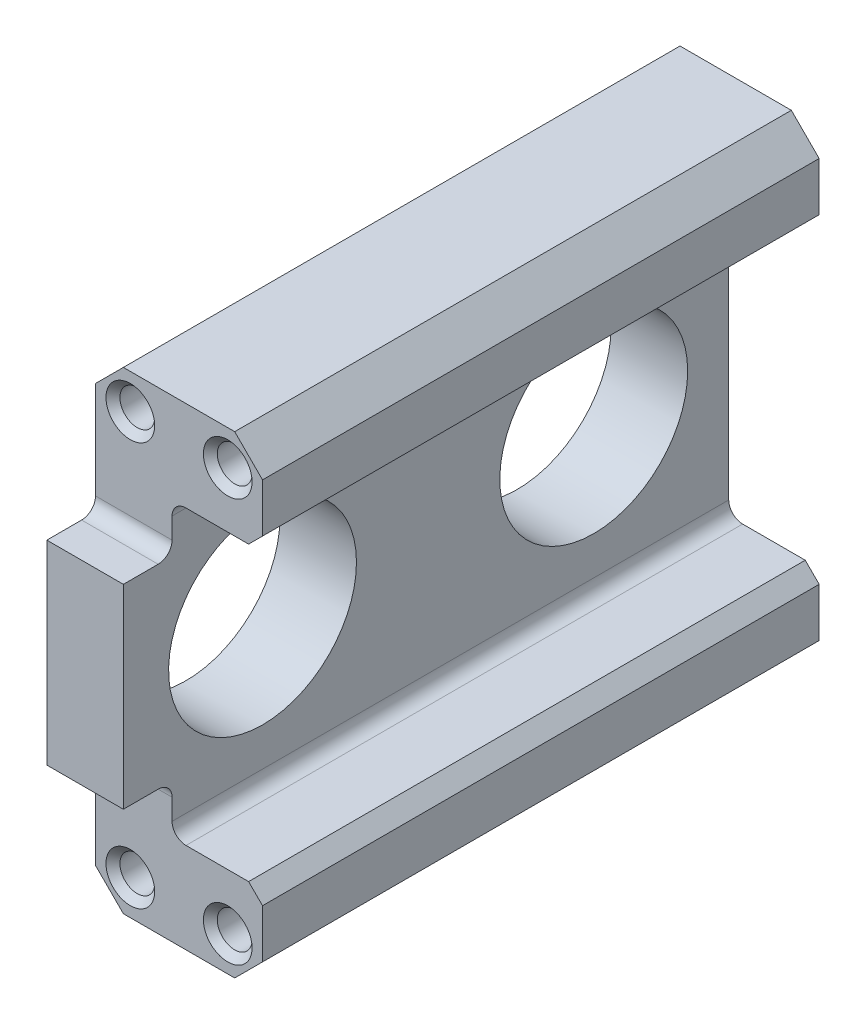
SolidWorks part; units mm, degrees
material "7075-O (SS)"
ref_plane "前视基准面" through (0, 0, 0) normal (0, 0, 1) x (1, 0, 0)
ref_plane "上视基准面" through (0, 0, 0) normal (0, 1, 0) x (1, 0, 0)
ref_plane "右视基准面" through (0, 0, 0) normal (1, 0, 0) x (0, 0, -1)
sketch "草图1" plane through (0, 0, 0) normal (0, 0, 1) x (1, 0, 0)
  line L1 (-6, -17) -> (6, -17)
  line L2 (-6, -17) -> (-6, 17)
  line L3 (-6, 17) -> (6, 17)
  line L4 (6, -17) -> (6, 17)
  line L5 (-6, -17) -> (6, 17) construction
  line L6 (-6, 17) -> (6, -17) construction
  point P0 (0, 0)
  dimension "D1" = 12
  dimension "D2" = 34
extrude "凸台-拉伸1" add sketch "草图1" along normal blind 43.5
sketch "草图3" plane through (6, 0, 0) normal (1, 0, 0) x (0, 0, -1)
  line L0 (-43.5, -17) -> (-43.5, 17) construction
  circle A0 centre (-33.5, 0) radius 6.75
  circle A1 centre (-9.7, 0) radius 6.75
  dimension "D1" = 13.5
  dimension "D2" = 10
  dimension "D3" = 33.8
extrude "切除-拉伸1" cut sketch "草图3" against normal through all
sketch "草图4" plane through (0, 0, 43.5) normal (0, 0, 1) x (1, 0, 0)
  line L0 (-6, 17) -> (-6, -17) construction
  line L1 (6, 17) -> (-6, 17)
  line L2 (6, 17) -> (6, 7)
  line L3 (6, 7) -> (-6, 7)
  line L4 (-6, 17) -> (-6, 7)
  dimension "D1" = 10
extrude "切除-拉伸2" cut sketch "草图4" against normal blind 3.5
mirror "镜向1" about plane through (0, 0, 0) normal (0, 1, 0) of "切除-拉伸2"
fillet "圆角1" radius 1 2 edges at (0, -7, 40) (0, 7, 40)
hole_wizard "M3 螺纹孔1" positions "草图6" profile "草图5" tap size "M3" standard "GB"
sketch "草图6" plane through (0, 0, 40) normal (0, 0, 1) x (1, 0, 0)
  point P0 (3.5, 14.5)
  point P2 (-3.5, 14.5)
  dimension "D1" = 7
  dimension "D2" = 3.5
  dimension "D3" = 14.5
sketch "草图5" plane through (3.5, 14.5, 40) normal (1, 0, 0) x (0, -1, 0)
  line L0 (0, 0) -> (0, 10.2511)
  line L1 (0, 10.2511) -> (1.25, 9.5)
  line L2 (1.25, 9.5) -> (1.25, 0)
  line L5 (1.25, 0) -> (0, 0)
  line L10 (0, 10.2511) -> (-1.25, 9.5) construction
  line L11 (0, -6.35) -> (0, 107.95) construction
  dimension "螺纹孔钻头直径" = 2.5
  dimension "螺纹孔钻头深度" = 9.5
  dimension "导头角度" = 118
cosmetic thread "孔螺蚊线1" parameters "D1"=8, "D2"=3
cosmetic thread "孔螺蚊线2" parameters "D1"=8, "D2"=3
mirror "镜向2" about plane through (0, 0, 0) normal (0, 1, 0) of "M3 螺纹孔1"
chamfer "倒角1" distance 0.5 angle 45 4 edges at (-2.25, 14.5, 40) (4.75, 14.5, 40) (-2.25, -14.5, 40) (4.75, -14.5, 40)
sketch "草图7" plane through (0, 0, 0) normal (0, 0, -1) x (-1, 0, 0)
  line L0 (-6, -17) -> (-6, 17) construction
  line L1 (-12.5, 10.5) -> (0.5, 10.5)
  line L2 (-12.5, 10.5) -> (-12.5, -10.5)
  line L3 (-12.5, -10.5) -> (0.5, -10.5)
  line L4 (0.5, 10.5) -> (0.5, -10.5)
  line L5 (-12.5, 10.5) -> (0.5, -10.5) construction
  line L6 (-12.5, -10.5) -> (0.5, 10.5) construction
  point P0 (-6, 0)
  dimension "D1" = 21
  dimension "D2" = 13
extrude "切除-拉伸3" cut sketch "草图7" against normal through all
chamfer "倒角2" distance 2 angle 45 4 edges at (6, 17, 20) (6, -17, 20) (-6, -17, 20) (-6, 17, 20)
chamfer "倒角3" distance 1 angle 45 2 edges at (6, -10.5, 20) (6, 10.5, 20)
fillet "圆角2" radius 1 2 edges at (-0.5, 10.5, 20) (-0.5, -10.5, 20)
sketch "草图8" plane through (0, 0, 0) normal (0, 0, -1) x (-1, 0, 0)
  line L0 (-4, 17) -> (4, 17)
  line L1 (4, 17) -> (6, 15)
  line L2 (6, 15) -> (6, -15)
  line L3 (6, -15) -> (4, -17)
  line L4 (4, -17) -> (-4, -17)
  line L5 (4, -17) -> (-4, -17) construction
  line L6 (-4, -17) -> (-6, -15)
  line L7 (-6, -15) -> (-4, -17) construction
  line L8 (-6, -15) -> (-6, -11.5)
  line L9 (-6, -11.5) -> (-5, -10.5)
  line L10 (-5, -10.5) -> (0.5, -10.5)
  line L11 (0.5, 10.5086) -> (-5, 10.5)
  line L12 (-5, 10.5) -> (-6, 11.5)
  line L13 (-6, 11.5) -> (-6, 15)
  line L14 (-6, 15) -> (-4, 17)
  line L15 (0.5, 10.5086) -> (0.5, -10.5)
extrude "凸台-拉伸2" [suppressed] add sketch "草图8" along normal blind 8
fillet "圆角3" [suppressed] radius 1
sketch "草图9" [suppressed] plane through (0, 0, -8) normal (0, 0, -1) x (-1, 0, 0)
  line L0 (0.5, 0.0035) -> (7.25, 0.0035)
  line L1 (0.5, 9.5071) -> (0.5, -9.5) construction
hole_wizard "M3 螺纹孔2" [suppressed] positions "3D草图2" profile "草图11" tap size "M3" standard "GB"
sketch3d "3D草图2" [suppressed]
  point P0 (-7.25, 0.0035, -8)
sketch "草图11" plane through (-7.25, 0.0035, -8) normal (1, 0, 0) x (0, 1, 0)
  line L0 (0, 0) -> (0, 10.2511)
  line L1 (0, 10.2511) -> (1.25, 9.5)
  line L2 (1.25, 9.5) -> (1.25, 0)
  line L5 (1.25, 0) -> (0, 0)
  line L10 (0, 10.2511) -> (-1.25, 9.5) construction
  line L11 (0, -6.35) -> (0, 107.95) construction
  dimension "螺纹孔钻头直径" = 2.5
  dimension "螺纹孔钻头深度" = 9.5
  dimension "导头角度" = 118
sketch "草图12" [suppressed] plane through (-6, 0, 0) normal (-1, 0, 0) x (0, 0, 1)
  line L0 (-8, -15) -> (-8, 15)
  line L1 (-8, 15) -> (40, 15)
  line L2 (40, 15) -> (40, 7)
  line L3 (40, 7) -> (43.5, 7)
  line L4 (43.5, 7) -> (43.5, -7)
  line L5 (43.5, -7) -> (40, -7)
  line L6 (40, -7) -> (40, -15)
  line L7 (40, -15) -> (-8, -15)
  circle A0 centre (10.5, 0) radius 7.5
  circle A1 centre (33.5, 0) radius 7.5
extrude "凸台-拉伸3" [suppressed] add sketch "草图12" along normal blind 4
fillet "圆角4" [suppressed] radius 1
chamfer "倒角4" [suppressed] distance 2 angle 45
sketch "草图13" [suppressed] plane through (0, 0, -8) normal (0, 0, -1) x (-1, 0, 0)
  line L0 (6, 15) -> (6, 13)
  line L1 (6, 13) -> (10, 13)
  line L2 (10, 13) -> (10, 15)
  line L3 (10, 15) -> (6, 15)
  line L4 (6, -15) -> (6, -13)
  line L5 (6, -13) -> (10, -13)
  line L6 (10, -13) -> (10, -15)
  line L7 (10, -15) -> (6, -15)
extrude "切除-拉伸4" [suppressed] cut sketch "草图13" against normal through all
fillet "圆角5" [suppressed] radius 1
chamfer "倒角5" [suppressed] distance 1 angle 45
hole_wizard "M3 螺纹孔3" [suppressed] positions "3D草图3" profile "草图14" tap size "M3" standard "GB"
sketch3d "3D草图3" [suppressed]
  point P0 (-7.25, 0.0035, -8)
sketch "草图14" plane through (-7.25, 0.0035, -8) normal (1, 0, 0) x (0, 1, 0)
  line L0 (0, 0) -> (0, 7.2511)
  line L1 (0, 7.2511) -> (1.25, 6.5)
  line L2 (1.25, 6.5) -> (1.25, 0)
  line L5 (1.25, 0) -> (0, 0)
  line L10 (0, 7.2511) -> (-1.25, 6.5) construction
  line L11 (0, -6.35) -> (0, 107.95) construction
  dimension "螺纹孔钻头直径" = 2.5
  dimension "螺纹孔钻头深度" = 6.5
  dimension "导头角度" = 118
cosmetic thread "孔螺蚊线3" parameters "D1"=5, "D2"=3
sketch "草图16" [suppressed] plane through (0, 0, -8) normal (0, 0, -1) x (-1, 0, 0)
  line L0 (0.5, 0.0035) -> (4.5, 0.0035) construction
  line L1 (0.5, 9.5071) -> (0.5, -9.5) construction
  line L2 (0.5, 0.0035) -> (7.25, 0.0035) construction
  line L3 (4.5, 0.0035) -> (4.5, 10.5035)
  line L4 (4.5, 10.5035) -> (-0.5016, 10.5071)
  line L5 (-0.5016, 10.5071) -> (-0.5, -10.5)
  line L6 (-0.5, -10.5) -> (-5, -10.5) construction
  line L7 (-0.5, -10.5) -> (4.5, -10.5)
  line L8 (4.5, -10.5) -> (4.5, 0.0035)
  arc A0 (-0.5, -10.5) -> (0.5, -9.5) centre (-0.5, -9.5) ccw construction
extrude "切除-拉伸5" [suppressed] cut sketch "草图16" against normal through all
sketch "草图17" [suppressed] plane through (0, 0, -8) normal (0, 0, -1) x (-1, 0, 0)
  line L0 (-6.4764, 18.6782) -> (12.2172, 18.6782)
  line L1 (12.2172, 18.6782) -> (12.2172, 10.5035)
  line L2 (11.6083, -10.4916) -> (4.5, -10.5)
  line L3 (-6.4764, 10.5053) -> (-6.4764, 18.6782)
  line L4 (4.5, -10.5) -> (4.5, -8.6142)
  line L5 (4.5, -10.5) -> (4.5, 10.5035) construction
  line L6 (-6.464, -10.5129) -> (-6.4538, -19.2029)
  line L7 (4.5, -8.6142) -> (-6.464, -8.1429)
  line L8 (11.6185, -19.1816) -> (11.6083, -10.4916)
  line L9 (-6.4538, -19.2029) -> (11.6185, -19.1816)
  line L10 (-6.464, -8.1429) -> (-6.464, -10.5129)
  line L11 (12.2172, 10.5035) -> (4.5, 10.5035)
  line L12 (4.5, 10.5035) -> (4.5, 8.5121)
  line L13 (4.5, 8.5121) -> (-6.4764, 8.9839)
  line L14 (-6.4764, 8.9839) -> (-6.4764, 10.5053)
  line L15 (4.5, 10.5035) -> (-0.4993, 10.5071) construction
extrude "切除-拉伸9" [suppressed] cut sketch "草图17" against normal blind 35
fillet "圆角6" [suppressed] radius 1
